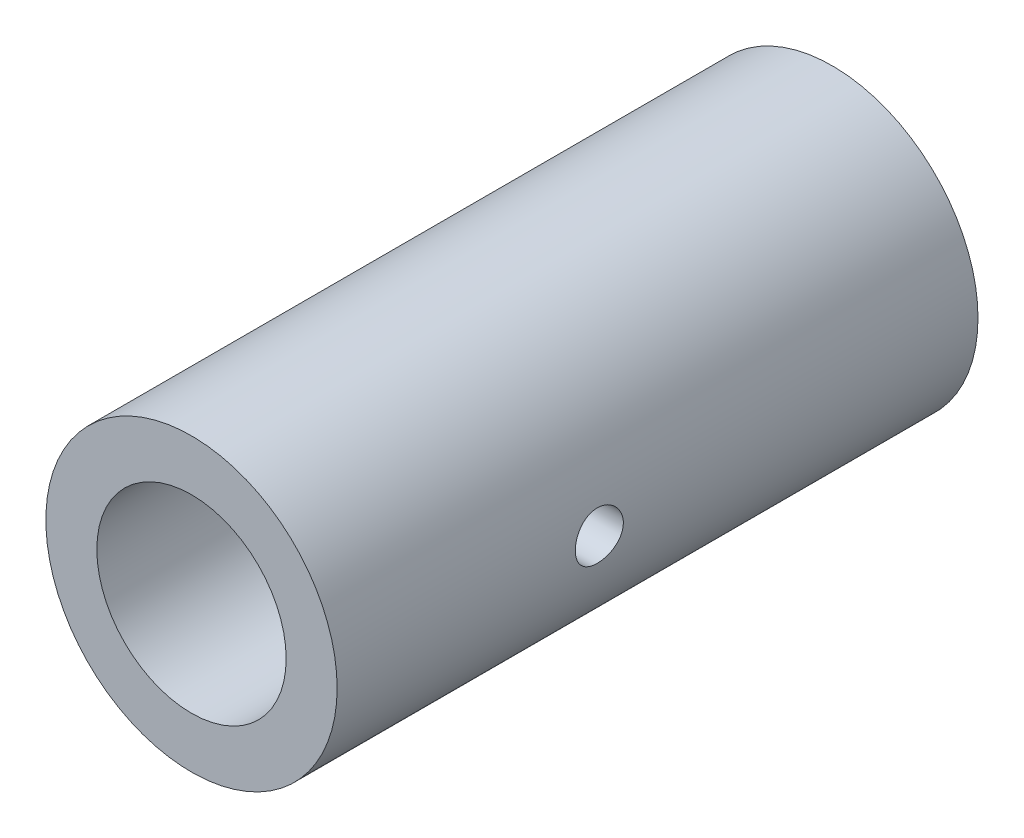
SolidWorks part; units mm, degrees
material "3.1355 (EN-AW 2024)"
ref_plane "Front" through (0, 0, 0) normal (0, 0, 1) x (1, 0, 0)
ref_plane "Top" through (0, 0, 0) normal (0, 1, 0) x (1, 0, 0)
ref_plane "Right" through (0, 0, 0) normal (1, 0, 0) x (0, 0, -1)
sketch "Эскиз1" plane through (0, 0, 0) normal (0, 0, 1) x (1, 0, 0)
  circle A0 centre (0, 0) radius 10
  dimension "D1" = 20
extrude "Бобышка-Вытянуть1" add sketch "Эскиз1" along normal blind 44
sketch "Эскиз2" plane through (0, 0, 44) normal (0, 0, 1) x (1, 0, 0)
  circle A0 centre (0, 0) radius 6.5
  dimension "D1" = 13
extrude "Вырез-Вытянуть1" cut sketch "Эскиз2" against normal blind 27
sketch "Эскиз3" plane through (0, 0, 0) normal (0, 1, 0) x (1, 0, 0)
  line L0 (-10, -44) -> (-10, -26) construction
  dimension "D1" = 18
ref_plane "Плоскость1" through (-10, 0, 0) normal (1, 0, 0) x (0, 0, -1)
hole_wizard "Отверстие обработанное метчиком M4x0.71" positions "Эскиз5" profile "Эскиз4" tap size "M4x0.7" standard "Ansi Metric" end condition through all
sketch "Эскиз5" plane through (-10, 0, 0) normal (1, 0, 0) x (0, 0, -1)
  line L0 (-44, 0) -> (-26, 0) construction
  point P0 (-26, 0)
sketch "Эскиз4" plane through (-10, 0, 26) normal (0, 1, 0) x (0, 0, 1)
  line L0 (0, 0) -> (0, 20)
  line L1 (0, 20) -> (1.65, 20)
  line L2 (1.65, 20) -> (1.65, 0)
  line L5 (1.65, 0) -> (0, 0)
  line L11 (0, -6.35) -> (0, 107.95) construction
  dimension "Диаметр проходного сверла" = 3.3
  dimension "Глубина проходного сверла" = 20
cosmetic thread "Отверстие резьбы6" parameters "D2"=4
sketch "Эскиз7" plane through (0, 0, 0) normal (0, 0, -1) x (-1, 0, 0)
  line L0 (-6, 0) -> (0, 0) construction
  line L1 (0, 0) -> (-4.2426, 4.2426) construction
  line L2 (0, 0) -> (4.2426, 4.2426) construction
  line L3 (0, 0) -> (4.2426, -4.2426) construction
  line L4 (0, 0) -> (-4.2426, -4.2426) construction
  circle A0 centre (0, 0) radius 6 construction
  point P11 (0, 0)
  dimension "D1" = 12
  dimension "D2" = 45
  dimension "D3" = 4
hole_wizard "Отверстие обработанное метчиком M3x0.51" positions "Эскиз9" profile "Эскиз8" tap size "M3x0.5" standard "Ansi Metric"
sketch "Эскиз9" plane through (0, 0, 0) normal (0, 0, -1) x (-1, 0, 0)
  point P0 (-4.2426, 4.2426)
  point P3 (4.2426, 4.2426)
  point P6 (4.2426, -4.2426)
  point P9 (-4.2426, -4.2426)
cosmetic thread "Отверстие резьбы2" parameters "D1"=6, "D2"=3
cosmetic thread "Отверстие резьбы3" parameters "D1"=6, "D2"=3
cosmetic thread "Отверстие резьбы4" parameters "D1"=6, "D2"=3
cosmetic thread "Отверстие резьбы5" parameters "D1"=6, "D2"=3
sketch "Эскиз8" plane through (4.2426, 4.2426, 0) normal (1, 0, 0) x (0, 1, 0)
  line L0 (0, 0) -> (0, 9.2511)
  line L1 (0, 9.2511) -> (1.25, 8.5)
  line L2 (1.25, 8.5) -> (1.25, 0)
  line L5 (1.25, 0) -> (0, 0)
  line L10 (0, 9.2511) -> (-1.25, 8.5) construction
  line L11 (0, -6.35) -> (0, 107.95) construction
  dimension "Диаметр сверла" = 2.5
  dimension "Глубина сверла" = 8.5
  dimension "Угол заточки сверла" = 118
